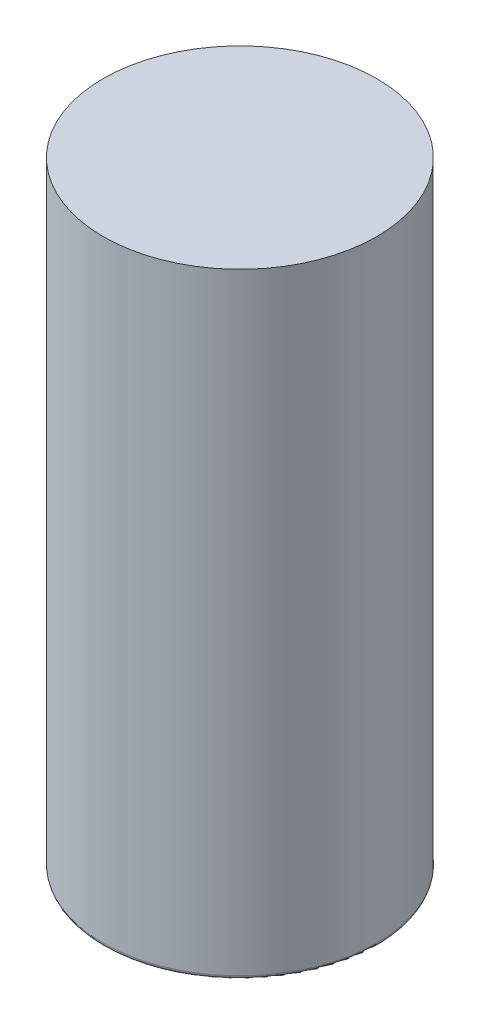
SolidWorks part; units mm, degrees
ref_plane "Front Plane" through (0, 0, 0) normal (0, 0, 1) x (1, 0, 0)
ref_plane "Top Plane" through (0, 0, 0) normal (0, 1, 0) x (1, 0, 0)
ref_plane "Right Plane" through (0, 0, 0) normal (1, 0, 0) x (0, 0, -1)
sketch "Sketch1" plane through (0, 0, 0) normal (0, 1, 0) x (1, 0, 0)
  circle A0 centre (0, 0) radius 9
extrude "Boss-Extrude1" add sketch "Sketch1" along normal blind 40.5
fillet "Fillet1" radius 0.254 1 edges at (0, 0, 9)
